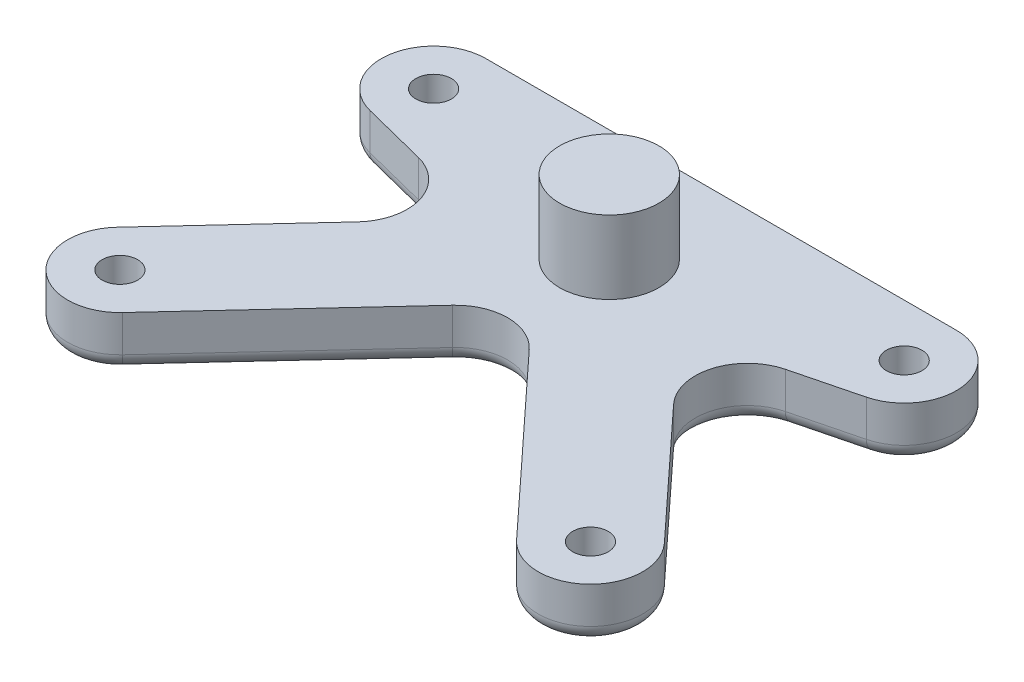
SolidWorks part; units mm, degrees
ref_plane "Front Plane" through (0, 0, 0) normal (0, 0, 1) x (1, 0, 0)
ref_plane "Top Plane" through (0, 0, 0) normal (0, 1, 0) x (1, 0, 0)
ref_plane "Right Plane" through (0, 0, 0) normal (1, 0, 0) x (0, 0, -1)
sketch "Sketch1" plane through (0, 0, 0) normal (0, 1, 0) x (1, 0, 0)
  line L0 (22.5, 15) -> (-22.5, 15) construction
  line L1 (-22.5, 15) -> (-22.5, -15) construction
  line L2 (-22.5, -15) -> (22.5, -15) construction
  line L3 (22.5, -15) -> (22.5, 15) construction
  line L4 (-22.5, -15) -> (0, 9.3) construction
  line L5 (-26.1688, -11.603) -> (-15.1071, 0.3436)
  line L6 (-18.8312, -18.397) -> (-3.6688, -2.0217)
  line L7 (0, 9.3) -> (22.5, -15) construction
  line L10 (22.5, 15) -> (0, 9.3) construction
  line L11 (23.7279, 10.1531) -> (17.5481, 8.5876)
  line L13 (-22.5, 15) -> (0, 9.3) construction
  line L15 (-23.7279, 10.1531) -> (-17.5481, 8.5876)
  line L16 (-22.5, 20) -> (22.5, 20)
  line L17 (15.1071, 0.3436) -> (26.1688, -11.603)
  line L18 (3.6688, -2.0217) -> (18.8312, -18.397)
  circle A0 centre (22.5, 15) radius 1.7
  circle A1 centre (22.5, -15) radius 1.7
  circle A2 centre (-22.5, 15) radius 1.7
  circle A3 centre (-22.5, -15) radius 1.7
  circle A4 centre (0, 9.3) radius 4.75 construction
  arc A5 (-26.1688, -11.603) -> (-18.8312, -18.397) centre (-22.5, -15) ccw
  arc A8 (18.8312, -18.397) -> (26.1688, -11.603) centre (22.5, -15) ccw
  arc A9 (23.7279, 10.1531) -> (22.5, 20) centre (22.5, 15) ccw
  arc A11 (-22.5, 20) -> (-23.7279, 10.1531) centre (-22.5, 15) ccw
  arc A12 (15.1071, 0.3436) -> (17.5481, 8.5876) centre (18.7759, 3.7407) cw
  arc A13 (-15.1071, 0.3436) -> (-17.5481, 8.5876) centre (-18.7759, 3.7407) ccw
  arc A14 (3.6688, -2.0217) -> (-3.6688, -2.0217) centre (0, -5.4187) ccw
  point P7 (-22.5, 0)
  point P9 (-11.25, -2.85)
  point P11 (0, 15)
  point P18 (11.25, -2.85)
  point P24 (11.25, 12.15)
  point P30 (-11.25, 12.15)
  dimension "D1" = 3.4
  dimension "D2" = 3.4
  dimension "D3" = 3.4
  dimension "D4" = 3.4
  dimension "D7" = 9.5
  dimension "D9" = 5
  dimension "D10" = 5
  dimension "D11" = 5
  dimension "D12" = 5
  dimension "D13" = 5
  dimension "D14" = 5
  dimension "D5" = 45
  dimension "D6" = 30
  dimension "D8" = 24.3
  dimension "D15" = 37.5519
  dimension "D16" = 5.5593
  dimension "D17" = 6.1798
  dimension "D18" = 1.5656
  dimension "D19" = 1.5656
  dimension "D20" = 6.1798
  dimension "D21" = 11.9466
  dimension "D22" = 11.9466
  dimension "D23" = 85.595
  dimension "D24" = 15.1624
  dimension "D25" = 16.3754
  dimension "D26" = 15.1624
extrude "Boss-Extrude1" add sketch "Sketch1" along normal blind 5
sketch "Sketch2" plane through (0, 5, 0) normal (0, 1, 0) x (1, 0, 0)
  circle A0 centre (0, 9.3) radius 4.75
  circle A1 centre (-22.5, -15) radius 1.7 construction
  dimension "D1" = 9.5
  dimension "D2" = 24.3
extrude "Boss-Extrude2" add sketch "Sketch2" along normal blind 7
fillet "Fillet1" radius 1.5 14 edges at (27.4616, 0, -15.6187) (20.638, 0, -9.3703) (13.9817, 0, -5.1602) (20.638, 0, 5.6297) (25.897, 0, 18.6688) (11.25, 0, 10.2093) (0, 0, 0.4187) (-11.25, 0, 10.2093) (-25.897, 0, 18.6688) (-20.638, 0, 5.6297) (-13.9817, 0, -5.1602) (-20.638, 0, -9.3703) (-27.4616, 0, -15.6187) (0, 0, -20)
